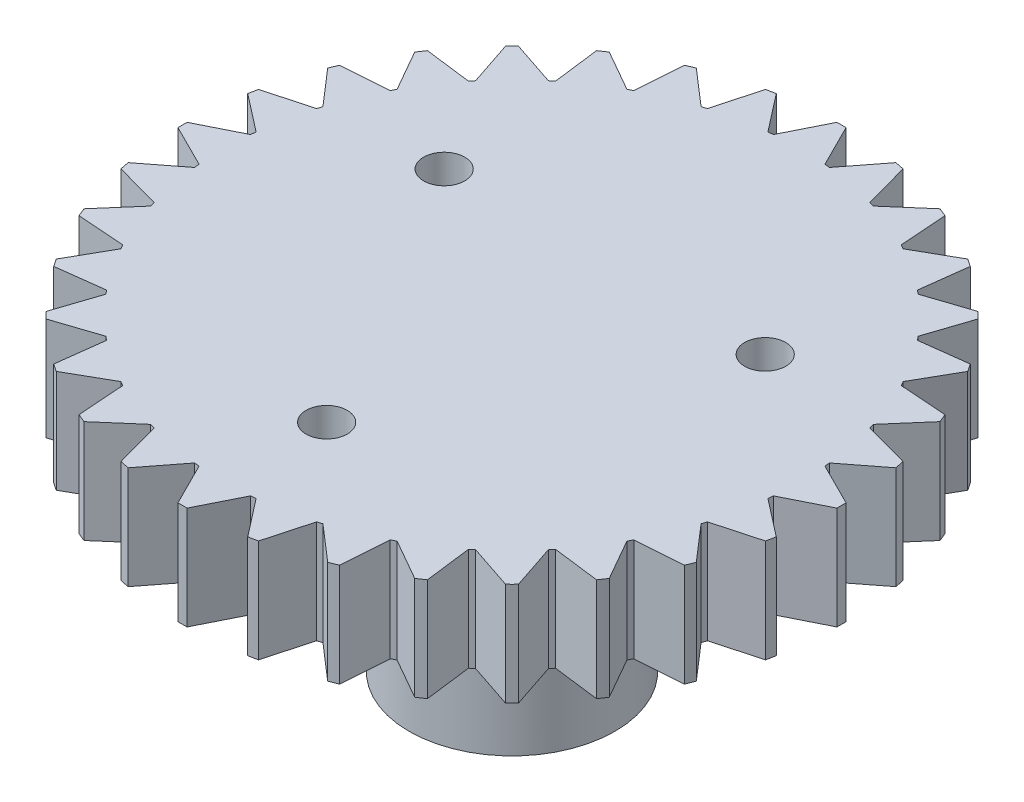
SolidWorks part; units mm, degrees
ref_plane "Front Plane" through (0, 0, 0) normal (0, 0, 1) x (1, 0, 0)
ref_plane "Top Plane" through (0, 0, 0) normal (0, 1, 0) x (1, 0, 0)
ref_plane "Right Plane" through (0, 0, 0) normal (1, 0, 0) x (0, 0, -1)
sketch "Sketch1" plane through (0, 0, 0) normal (0, 1, 0) x (1, 0, 0)
  line L0 (0, 17.709) -> (0, 17.78) construction
  line L1 (0, 20.884) -> (1.5875, 17.709)
  line L2 (0, 20.884) -> (-1.5875, 17.709)
  line L4 (4.0743, 20.4827) -> (1.8979, 17.6784)
  line L5 (4.0743, 20.4827) -> (5.0118, 17.059)
  line L6 (7.992, 19.2943) -> (5.3103, 16.9685)
  line L7 (7.992, 19.2943) -> (8.2436, 15.7535)
  line L8 (11.6025, 17.3644) -> (8.5186, 15.6065)
  line L9 (11.6025, 17.3644) -> (11.1585, 13.8425)
  line L10 (14.7672, 14.7672) -> (11.3996, 13.6447)
  line L11 (14.7672, 14.7672) -> (13.6447, 11.3996)
  line L12 (17.3644, 11.6025) -> (13.8425, 11.1585)
  line L13 (17.3644, 11.6025) -> (15.6065, 8.5186)
  line L14 (19.2943, 7.992) -> (15.7535, 8.2436)
  line L15 (19.2943, 7.992) -> (16.9685, 5.3103)
  line L16 (20.4827, 4.0743) -> (17.059, 5.0118)
  line L17 (20.4827, 4.0743) -> (17.6784, 1.8979)
  line L18 (20.884, 0) -> (17.709, 1.5875)
  line L19 (20.884, 0) -> (17.709, -1.5875)
  line L20 (20.4827, -4.0743) -> (17.6784, -1.8979)
  line L21 (20.4827, -4.0743) -> (17.059, -5.0118)
  line L22 (19.2943, -7.992) -> (16.9685, -5.3103)
  line L23 (19.2943, -7.992) -> (15.7535, -8.2436)
  line L24 (17.3644, -11.6025) -> (15.6065, -8.5186)
  line L25 (17.3644, -11.6025) -> (13.8425, -11.1585)
  line L26 (14.7672, -14.7672) -> (13.6447, -11.3996)
  line L27 (14.7672, -14.7672) -> (11.3996, -13.6447)
  line L28 (11.6025, -17.3644) -> (11.1585, -13.8425)
  line L29 (11.6025, -17.3644) -> (8.5186, -15.6065)
  line L30 (7.992, -19.2943) -> (8.2436, -15.7535)
  line L31 (7.992, -19.2943) -> (5.3103, -16.9685)
  line L32 (4.0743, -20.4827) -> (5.0118, -17.059)
  line L33 (4.0743, -20.4827) -> (1.8979, -17.6784)
  line L34 (0, -20.884) -> (1.5875, -17.709)
  line L35 (0, -20.884) -> (-1.5875, -17.709)
  line L36 (-4.0743, -20.4827) -> (-1.8979, -17.6784)
  line L37 (-4.0743, -20.4827) -> (-5.0118, -17.059)
  line L38 (-7.992, -19.2943) -> (-5.3103, -16.9685)
  line L39 (-7.992, -19.2943) -> (-8.2436, -15.7535)
  line L40 (-11.6025, -17.3644) -> (-8.5186, -15.6065)
  line L41 (-11.6025, -17.3644) -> (-11.1585, -13.8425)
  line L42 (-14.7672, -14.7672) -> (-11.3996, -13.6447)
  line L43 (-14.7672, -14.7672) -> (-13.6447, -11.3996)
  line L44 (-17.3644, -11.6025) -> (-13.8425, -11.1585)
  line L45 (-17.3644, -11.6025) -> (-15.6065, -8.5186)
  line L46 (-19.2943, -7.992) -> (-15.7535, -8.2436)
  line L47 (-19.2943, -7.992) -> (-16.9685, -5.3103)
  line L48 (-20.4827, -4.0743) -> (-17.059, -5.0118)
  line L49 (-20.4827, -4.0743) -> (-17.6784, -1.8979)
  line L50 (-20.884, 0) -> (-17.709, -1.5875)
  line L51 (-20.884, 0) -> (-17.709, 1.5875)
  line L52 (-20.4827, 4.0743) -> (-17.6784, 1.8979)
  line L53 (-20.4827, 4.0743) -> (-17.059, 5.0118)
  line L54 (-19.2943, 7.992) -> (-16.9685, 5.3103)
  line L55 (-19.2943, 7.992) -> (-15.7535, 8.2436)
  line L56 (-17.3644, 11.6025) -> (-15.6065, 8.5186)
  line L57 (-17.3644, 11.6025) -> (-13.8425, 11.1585)
  line L58 (-14.7672, 14.7672) -> (-13.6447, 11.3996)
  line L59 (-14.7672, 14.7672) -> (-11.3996, 13.6447)
  line L60 (-11.6025, 17.3644) -> (-11.1585, 13.8425)
  line L61 (-11.6025, 17.3644) -> (-8.5186, 15.6065)
  line L62 (-7.992, 19.2943) -> (-8.2436, 15.7535)
  line L63 (-7.992, 19.2943) -> (-5.3103, 16.9685)
  line L64 (-4.0743, 20.4827) -> (-5.0118, 17.059)
  line L65 (-4.0743, 20.4827) -> (-1.8979, 17.6784)
  arc A0 (-1.5875, 17.709) -> (-1.8979, 17.6784) centre (0, 0) ccw
  arc A1 (-5.0118, 17.059) -> (-5.3103, 16.9685) centre (0, 0) ccw
  arc A2 (-8.2436, 15.7535) -> (-8.5186, 15.6065) centre (0, 0) ccw
  arc A3 (-11.1585, 13.8425) -> (-11.3996, 13.6447) centre (0, 0) ccw
  arc A4 (-13.6447, 11.3996) -> (-13.8425, 11.1585) centre (0, 0) ccw
  arc A5 (-15.6065, 8.5186) -> (-15.7535, 8.2436) centre (0, 0) ccw
  arc A6 (-16.9685, 5.3103) -> (-17.059, 5.0118) centre (0, 0) ccw
  arc A7 (-17.6784, 1.8979) -> (-17.709, 1.5875) centre (0, 0) ccw
  arc A8 (-17.709, -1.5875) -> (-17.6784, -1.8979) centre (0, 0) ccw
  arc A9 (-17.059, -5.0118) -> (-16.9685, -5.3103) centre (0, 0) ccw
  arc A10 (-15.7535, -8.2436) -> (-15.6065, -8.5186) centre (0, 0) ccw
  arc A11 (-13.8425, -11.1585) -> (-13.6447, -11.3996) centre (0, 0) ccw
  arc A12 (-11.3996, -13.6447) -> (-11.1585, -13.8425) centre (0, 0) ccw
  arc A13 (-8.5186, -15.6065) -> (-8.2436, -15.7535) centre (0, 0) ccw
  arc A14 (-5.3103, -16.9685) -> (-5.0118, -17.059) centre (0, 0) ccw
  arc A15 (-1.8979, -17.6784) -> (-1.5875, -17.709) centre (0, 0) ccw
  arc A16 (1.5875, -17.709) -> (1.8979, -17.6784) centre (0, 0) ccw
  arc A17 (5.0118, -17.059) -> (5.3103, -16.9685) centre (0, 0) ccw
  arc A18 (8.2436, -15.7535) -> (8.5186, -15.6065) centre (0, 0) ccw
  arc A19 (11.1585, -13.8425) -> (11.3996, -13.6447) centre (0, 0) ccw
  arc A20 (13.6447, -11.3996) -> (13.8425, -11.1585) centre (0, 0) ccw
  arc A21 (15.6065, -8.5186) -> (15.7535, -8.2436) centre (0, 0) ccw
  arc A22 (17.6784, -1.8979) -> (17.709, -1.5875) centre (0, 0) ccw
  arc A23 (16.9685, -5.3103) -> (17.059, -5.0118) centre (0, 0) ccw
  arc A24 (17.709, 1.5875) -> (17.6784, 1.8979) centre (0, 0) ccw
  arc A25 (17.059, 5.0118) -> (16.9685, 5.3103) centre (0, 0) ccw
  arc A26 (15.7535, 8.2436) -> (15.6065, 8.5186) centre (0, 0) ccw
  arc A27 (13.8425, 11.1585) -> (13.6447, 11.3996) centre (0, 0) ccw
  arc A28 (11.3996, 13.6447) -> (11.1585, 13.8425) centre (0, 0) ccw
  arc A29 (8.5186, 15.6065) -> (8.2436, 15.7535) centre (0, 0) ccw
  arc A30 (5.3103, 16.9685) -> (5.0118, 17.059) centre (0, 0) ccw
  arc A31 (1.8979, 17.6784) -> (1.5875, 17.709) centre (0, 0) ccw
  dimension "D1" = 35.56
  dimension "D2" = 3.175
  dimension "D3" = 3.175
  dimension "D4" = 32
extrude "Boss-Extrude1" add sketch "Sketch1" along normal blind 6.35
sketch "Sketch2" plane through (0, 6.35, 0) normal (0, 1, 0) x (-1, 0, 0)
  circle A0 centre (0, 0) radius 20.32
  dimension "D1" = 40.64
extrude "Cut-Extrude1" cut sketch "Sketch2" against normal through all flip side to cut
sketch "Sketch3" plane through (0, 0, 0) normal (0, -1, 0) x (1, 0, 0)
  circle A0 centre (0, 0) radius 6.35
  dimension "D1" = 12.7
extrude "Boss-Extrude2" add sketch "Sketch3" along normal blind 12.7
sketch "Sketch4" plane through (0, 0, 0) normal (0, -1, 0) x (1, 0, 0)
  line L0 (0, 0) -> (0, 11.43) construction
  line L2 (3.6662, 11.43) -> (1.8331, 14.605)
  line L3 (1.8331, 14.605) -> (-1.8331, 14.605)
  line L4 (-1.8331, 14.605) -> (-3.6662, 11.43)
  line L5 (-3.6662, 11.43) -> (-1.8331, 8.255)
  line L6 (-1.8331, 8.255) -> (1.8331, 8.255)
  line L7 (1.8331, 8.255) -> (3.6662, 11.43)
  circle A0 centre (0, 11.43) radius 3.175 construction
  dimension "D1" = 11.43
  dimension "D3" = 6.35
extrude "Cut-Extrude3" cut sketch "Sketch4" against normal blind 2.54
sketch "Sketch7" plane through (0, 2.54, 0) normal (0, -1, 0) x (1, 0, 0)
  line L0 (3.6662, 11.43) -> (-3.6662, 11.43) construction
  circle A0 centre (0, 11.43) radius 1.27
  dimension "D1" = 2.54
extrude "Cut-Extrude4" cut sketch "Sketch7" against normal through all
pattern_circular "CirPattern2" count 3 over 360 about axis through (0, 0, 0) along (0, 1, 0) of "Cut-Extrude3", "Cut-Extrude4"
